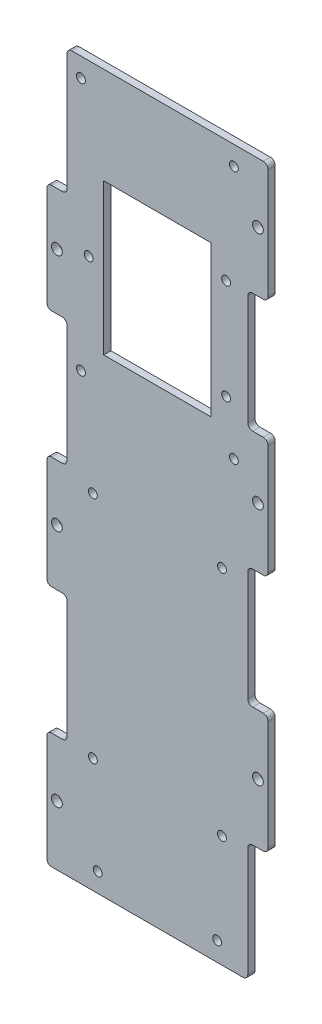
SolidWorks part; units mm, degrees
material "Acrylic (Medium-high impact)"
ref_plane "Front Plane" through (0, 0, 0) normal (0, 0, 1) x (1, 0, 0)
ref_plane "Top Plane" through (0, 0, 0) normal (0, 1, 0) x (1, 0, 0)
ref_plane "Right Plane" through (0, 0, 0) normal (1, 0, 0) x (0, 0, -1)
sketch "Sketch1" plane through (0, 0, 0) normal (0, 0, 1) x (1, 0, 0)
  line L1 (46.3, -150) -> (-46.3, -150)
  line L2 (46.3, -150) -> (46.3, 150)
  line L3 (46.3, 150) -> (-46.3, 150)
  line L4 (-46.3, -150) -> (-46.3, 150)
  line L5 (46.3, -150) -> (-46.3, 150) construction
  line L6 (46.3, 150) -> (-46.3, -150) construction
  point P0 (0, 0)
  dimension "D1" = 92.6
  dimension "D2" = 300
extrude "Boss-Extrude1" add sketch "Sketch1" along normal blind 3
sketch "Sketch2" plane through (0, 0, 0) normal (0, 0, 1) x (1, 0, 0)
  line L0 (-42.06, 150) -> (-42.06, -150) construction
  line L1 (46.3, 150) -> (-46.3, 150) construction
  line L2 (-46.3, -150) -> (46.3, -150) construction
  line L3 (42.06, 150) -> (42.06, -150) construction
  line L5 (-37.82, 97) -> (-46.3, 97)
  line L6 (-37.82, 97) -> (-37.82, 150)
  line L7 (-37.82, 150) -> (-46.3, 150)
  line L8 (-46.3, 97) -> (-46.3, 150)
  line L9 (-37.82, 97) -> (-46.3, 150) construction
  line L10 (-37.82, 150) -> (-46.3, 97) construction
  line L18 (46.3, -150) -> (46.3, 150) construction
  line L23 (37.82, 100) -> (46.3, 100)
  line L24 (37.82, 100) -> (37.82, 50)
  line L25 (37.82, 50) -> (46.3, 50)
  line L26 (46.3, 100) -> (46.3, 50)
  line L27 (37.82, 100) -> (46.3, 50) construction
  line L28 (37.82, 50) -> (46.3, 100) construction
  line L29 (46.3, -50) -> (37.82, -50)
  line L30 (46.3, -50) -> (46.3, 0)
  line L31 (46.3, 0) -> (37.82, 0)
  line L32 (37.82, -50) -> (37.82, 0)
  line L33 (46.3, -50) -> (37.82, 0) construction
  line L34 (46.3, 0) -> (37.82, -50) construction
  line L35 (-37.82, -1.5) -> (-46.3, -1.5)
  line L36 (-37.82, -1.5) -> (-37.82, 51.5)
  line L37 (-37.82, 51.5) -> (-46.3, 51.5)
  line L38 (-46.3, -1.5) -> (-46.3, 51.5)
  line L39 (-37.82, -1.5) -> (-46.3, 51.5) construction
  line L40 (-37.82, 51.5) -> (-46.3, -1.5) construction
  line L41 (-37.82, -101.5) -> (-46.3, -101.5)
  line L42 (-37.82, -101.5) -> (-37.82, -48.5)
  line L43 (-37.82, -48.5) -> (-46.3, -48.5)
  line L44 (-46.3, -101.5) -> (-46.3, -48.5)
  line L45 (-37.82, -101.5) -> (-46.3, -48.5) construction
  line L46 (-37.82, -48.5) -> (-46.3, -101.5) construction
  line L47 (37.82, -150) -> (46.3, -150)
  line L48 (37.82, -150) -> (37.82, -100)
  line L49 (37.82, -100) -> (46.3, -100)
  line L50 (46.3, -150) -> (46.3, -100)
  line L51 (37.82, -150) -> (46.3, -100) construction
  line L52 (37.82, -100) -> (46.3, -150) construction
  line L54 (42.06, 50) -> (-134.3061, 50) construction
  circle A0 centre (-42.06, 75) radius 2.25
  circle A1 centre (42.06, 125) radius 2.25
  circle A6 centre (42.06, 25) radius 2.25
  circle A7 centre (42.06, -75) radius 2.25
  circle A8 centre (-42.06, -25) radius 2.25
  circle A9 centre (-42.06, -125) radius 2.25
  point P12 (-42.06, 123.5)
  point P14 (-42.06, 25)
  point P24 (42.06, 75)
  point P29 (-42.06, -75)
  point P37 (42.06, -25)
  point P45 (42.06, -125)
  dimension "D1" = 4.5
  dimension "D2" = 4.5
  dimension "D19" = 75
  dimension "D20" = 4.5
  dimension "D22" = 4.5
  dimension "D25" = 4.5
  dimension "D29" = 4.5
  dimension "D4" = 75
  dimension "D5" = 25
  dimension "D6" = 84.12
  dimension "D7" = 42.06
  dimension "D9" = 8.48
  dimension "D10" = 53
  dimension "D11" = 26.5
  dimension "D3" = 53
  dimension "D13" = 8.48
  dimension "D14" = 8.48
  dimension "D15" = 50
  dimension "D16" = 100
  dimension "D17" = 50
  dimension "D18" = 100
  dimension "D8" = 8.48
  dimension "D21" = 25
  dimension "D23" = 175
  dimension "D24" = 125
  dimension "D12" = 53
  dimension "D26" = 100
  dimension "D27" = 50
  dimension "D28" = 25
  dimension "D30" = 25
  dimension "D31" = 8.48
extrude "Cut-Extrude5" cut sketch "Sketch2" along normal blind 10
fillet "Fillet3" radius 2 24 edges at (-46.3, 97, 1.5) (-37.82, 97, 1.5) (-37.82, 150, 1.5) (46.3, 150, 1.5) (46.3, 100, 1.5) (37.82, 100, 1.5) (37.82, 50, 1.5) (46.3, 50, 1.5) (46.3, 0, 1.5) (37.82, 0, 1.5) (37.82, -50, 1.5) (46.3, -50, 1.5) (46.3, -100, 1.5) (37.82, -100, 1.5) (37.82, -150, 1.5) (-46.3, -150, 1.5) (-46.3, -101.5, 1.5) (-37.82, -101.5, 1.5) (-37.82, -48.5, 1.5) (-46.3, -48.5, 1.5) (-46.3, -1.5, 1.5) (-37.82, -1.5, 1.5) (-37.82, 51.5, 1.5) (-46.3, 51.5, 1.5)
sketch "Sketch4" plane through (0, 0, 0) normal (0, 0, -1) x (-1, 0, 0)
  circle A0 centre (-25, -142) radius 1.85
  circle A1 centre (25, -142) radius 1.85
  circle A2 centre (32, 142) radius 1.85
  circle A3 centre (-32, 142) radius 1.85
  dimension "D1" = 3.7
extrude "Cut-Extrude6" cut sketch "Sketch4" against normal blind 10
sketch "Sketch5" plane through (0, 0, 0) normal (0, 0, -1) x (-1, 0, 0)
  circle A9 centre (-28.75, 99) radius 1.85
  circle A10 centre (28.75, 79.08) radius 1.85
  circle A11 centre (-28.75, 57) radius 1.85
  circle A12 centre (-32, 36) radius 1.85
  circle A13 centre (32, 36) radius 1.85
  circle A14 centre (-27, -6) radius 1.85
  circle A15 centre (27, -6) radius 1.85
  circle A16 centre (-27, -103.1567) radius 1.85
  circle A17 centre (27, -102) radius 1.85
  dimension "D1" = 3.7
  dimension "D2" = 3.7
  dimension "D3" = 3.7
  dimension "D4" = 3.7
  dimension "D5" = 3.7
  dimension "D6" = 3.7
  dimension "D7" = 3.7
  dimension "D8" = 3.7
  dimension "D9" = 3.7
extrude "Cut-Extrude7" cut sketch "Sketch5" against normal blind 5
sketch "Sketch6" plane through (0, 0, 0) normal (0, 0, -1) x (-1, 0, 0)
  line L0 (0, 114.175) -> (0, 41.4033) construction
  line L7 (0, 118.8) -> (0, 109.55) construction
  line L8 (34, 109.55) -> (-34, 109.55) construction
  line L9 (22.5, 46.45) -> (-22.5, 46.45)
  line L10 (22.5, 46.45) -> (22.5, 109.55)
  line L11 (22.5, 109.55) -> (-22.5, 109.55)
  line L12 (-22.5, 46.45) -> (-22.5, 109.55)
  line L13 (22.5, 46.45) -> (-22.5, 109.55) construction
  line L14 (22.5, 109.55) -> (-22.5, 46.45) construction
  point P4 (0, 78)
  dimension "D1" = 45
  dimension "D2" = 63.1
extrude "Cut-Extrude8" cut sketch "Sketch6" against normal blind 10
